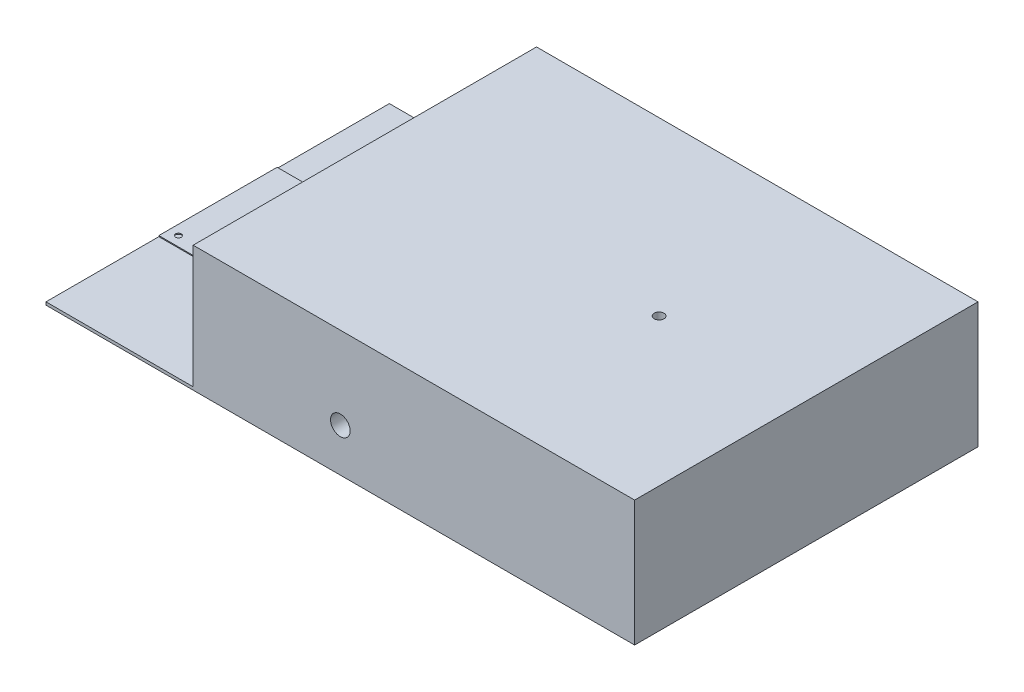
SolidWorks part; units mm, degrees
ref_plane "Front Plane" through (0, 0, 0) normal (0, 0, 1) x (1, 0, 0)
ref_plane "Top Plane" through (0, 0, 0) normal (0, 1, 0) x (1, 0, 0)
ref_plane "Right Plane" through (0, 0, 0) normal (1, 0, 0) x (0, 0, -1)
sketch "Sketch2" plane through (0, 0, 0) normal (0, 1, 0) x (1, 0, 0)
  line L1 (-300, 175) -> (300, 175)
  line L2 (-300, 175) -> (-300, -175)
  line L3 (-300, -175) -> (300, -175)
  line L4 (300, 175) -> (300, -175)
  line L5 (-300, 175) -> (300, -175) construction
  line L6 (-300, -175) -> (300, 175) construction
  point P0 (0, 0)
  dimension "D1" = 350
  dimension "D2" = 600
extrude "Boss-Extrude1" add sketch "Sketch2" along normal blind 3
sketch "Sketch3" plane through (0, 3, 0) normal (0, 1, 0) x (1, 0, 0)
  line L0 (-300, -175) -> (300, -175) construction
  line L1 (300, 175) -> (-150, 175)
  line L2 (300, 175) -> (300, -175)
  line L3 (300, -175) -> (-150, -175)
  line L4 (-150, 175) -> (-150, -175)
  dimension "D1" = 450
extrude "Boss-Extrude2" add sketch "Sketch3" along normal blind 125
sketch "Sketch4" plane through (0, 0, 175) normal (0, 0, 1) x (1, 0, 0)
  line L0 (-300, 0) -> (300, 0) construction
  circle A0 centre (0, 44) radius 10
  dimension "D1" = 20
  dimension "D2" = 44
extrude "Cut-Extrude1" cut sketch "Sketch4" against normal blind 350
sketch "Sketch6" plane through (0, 128, 0) normal (0, 1, 0) x (1, 0, 0)
  line L0 (300, -175) -> (300, 175) construction
  circle A0 centre (150, 0) radius 5
  dimension "D1" = 150
  dimension "D3" = 10
  dimension "D2" = 175
extrude "Cut-Extrude2" cut sketch "Sketch6" against normal blind 20
sketch "Sketch7" plane through (0, 3, 0) normal (0, 1, 0) x (1, 0, 0)
  line L0 (-300, 175) -> (-300, -175) construction
  line L1 (-300, 60.5778) -> (-180, 60.5778)
  line L2 (-300, 60.5778) -> (-300, -60)
  line L3 (-300, -60) -> (-180, -60)
  line L4 (-180, 60.5778) -> (-180, -60)
  line L7 (-300, -175) -> (-150, -175) construction
  circle A1 centre (-190, 50.5778) radius 3
  circle A2 centre (-290, -50) radius 3
  point P0 (-240, 0.2889)
  dimension "D5" = 10
  dimension "D1" = 0
  dimension "D2" = 120
  dimension "D3" = 120.5778
  dimension "D4" = 115
  dimension "D6" = 10
  dimension "D7" = 10
  dimension "D8" = 10
  dimension "D9" = 141.8305
extrude "Boss-Extrude3" add sketch "Sketch7" along normal mid plane 2
